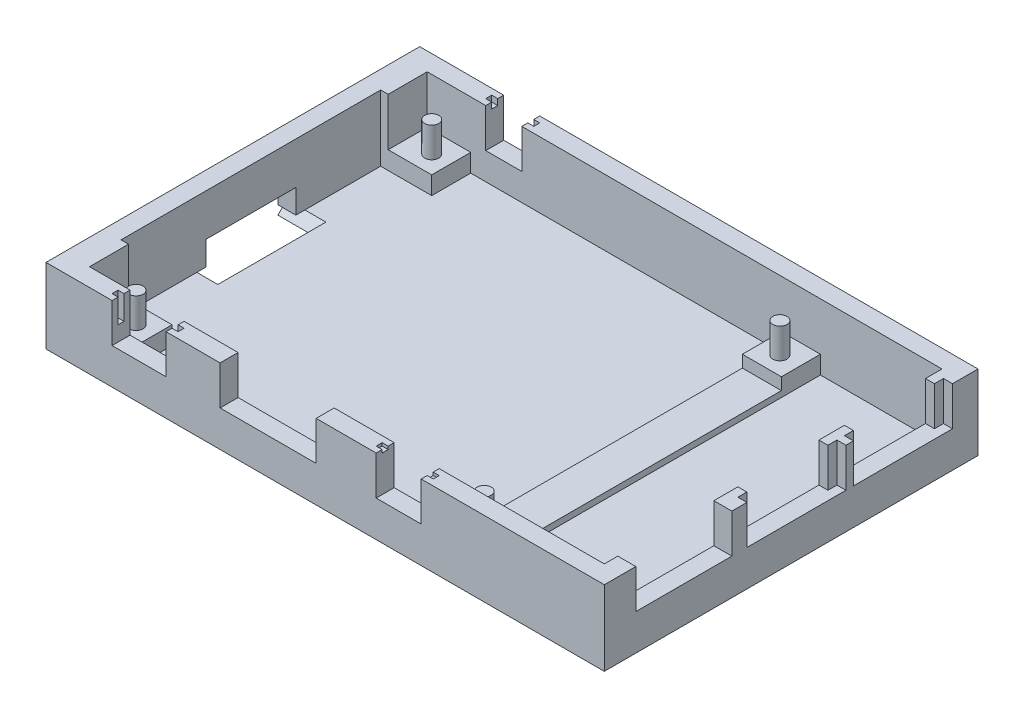
SolidWorks part; units mm, degrees
ref_plane "Front Plane" through (0, 0, 0) normal (0, 0, 1) x (1, 0, 0)
ref_plane "Top Plane" through (0, 0, 0) normal (0, 1, 0) x (1, 0, 0)
ref_plane "Right Plane" through (0, 0, 0) normal (1, 0, 0) x (0, 0, -1)
sketch "Sketch1" plane through (0, 0, 0) normal (0, 1, 0) x (1, 0, 0)
  line L1 (0, 0) -> (85, 0)
  line L2 (0, 0) -> (0, 56.25)
  line L3 (0, 56.25) -> (85, 56.25)
  line L4 (85, 0) -> (85, 56.25)
  dimension "D1" = 85
  dimension "D2" = 56.25
extrude "Boss-Extrude1" add sketch "Sketch1" along normal blind 1.5
sketch "Sketch2" plane through (0, 1.5, 0) normal (0, 1, 0) x (1, 0, 0)
  line L0 (0, 0) -> (85, 0) construction
  line L1 (0, 0) -> (6.5, 0)
  line L2 (0, 0) -> (0, 6.5)
  line L3 (0, 6.5) -> (6.5, 6.5)
  line L4 (6.5, 0) -> (6.5, 6.5)
  line L5 (58.25, 0) -> (64.75, 0)
  line L6 (58.25, 0) -> (58.25, 6.5)
  line L7 (58.25, 6.5) -> (64.75, 6.5)
  line L8 (64.75, 0) -> (64.75, 6.5)
  line L9 (61.5, 6.5) -> (61.5, 0) construction
  line L10 (0, 28.125) -> (85, 28.125) construction
  line L11 (0, 56.25) -> (0, 0) construction
  line L12 (85, 0) -> (85, 56.25) construction
  line L13 (61.5, 49.75) -> (61.5, 56.25) construction
  line L14 (64.75, 56.25) -> (64.75, 49.75)
  line L15 (58.25, 49.75) -> (64.75, 49.75)
  line L16 (58.25, 56.25) -> (58.25, 49.75)
  line L17 (58.25, 56.25) -> (64.75, 56.25)
  line L18 (6.5, 56.25) -> (6.5, 49.75)
  line L19 (0, 49.75) -> (6.5, 49.75)
  line L20 (0, 56.25) -> (0, 49.75)
  line L21 (0, 56.25) -> (6.5, 56.25)
  dimension "D1" = 6.5
  dimension "D2" = 6.5
  dimension "D3" = 6.5
  dimension "D4" = 61.5
extrude "Boss-Extrude2" add sketch "Sketch2" along normal blind 3
sketch "Sketch3" plane through (0, 4.5, 0) normal (0, 1, 0) x (1, 0, 0)
  line L0 (0, 6.5) -> (0, 0) construction
  line L3 (0, 28.125) -> (85, 28.125) construction
  line L4 (0, 49.75) -> (0, 6.5) construction
  line L5 (85, 0) -> (85, 56.25) construction
  line L6 (0, 0) -> (6.5, 0) construction
  line L9 (61.5, 0) -> (61.5, 6.5) construction
  line L12 (58.25, 0) -> (64.75, 0) construction
  line L13 (64.75, 6.5) -> (58.25, 6.5) construction
  circle A0 centre (3.5, 3.5) radius 1.175
  circle A1 centre (61.5, 3.5) radius 1.175
  circle A2 centre (61.5, 52.75) radius 1.175
  circle A3 centre (3.5, 52.75) radius 1.175
  dimension "D1" = 2.35
  dimension "D2" = 2.35
  dimension "D3" = 3.5
  dimension "D4" = 3.5
extrude "Boss-Extrude3" add sketch "Sketch3" along normal blind 5
sketch "Sketch4" plane through (0, 0, 0) normal (-1, 0, 0) x (0, 0, 1)
  line L0 (0, 4.5) -> (0, 0) construction
  line L1 (0, 1.5) -> (-56.25, 1.5)
  line L2 (0, 1.5) -> (0, 0)
  line L3 (0, 0) -> (-56.25, 0)
  line L4 (-56.25, 1.5) -> (-56.25, 0)
  dimension "D1" = 1.5
extrude "Boss-Extrude4" add sketch "Sketch4" along normal blind 5
sketch "Sketch5" plane through (0, 1.5, 0) normal (0, 1, 0) x (1, 0, 0)
  line L0 (-5, 56.25) -> (0, 56.25) construction
  line L1 (-5, 0) -> (-2.5, 0)
  line L2 (-5, 0) -> (-5, 56.25)
  line L3 (-5, 56.25) -> (-2.5, 56.25)
  line L4 (-2, 6.5) -> (-2, 49.75)
  line L6 (-2.5, 0) -> (0, 0)
  line L8 (-2, 6.5) -> (0, 6.5)
  line L9 (0, 0) -> (0, 6.5)
  line L10 (-2.5, 56.25) -> (0, 56.25)
  line L12 (-2, 49.75) -> (0, 49.75)
  line L13 (0, 56.25) -> (0, 49.75)
  dimension "D1" = 2
extrude "Boss-Extrude5" add sketch "Sketch5" along normal blind 11
sketch "Sketch6" plane through (0, 0, 0) normal (0, 1, 0) x (1, 0, 0)
  line L0 (85, 0) -> (85, 56.25) construction
  line L1 (-5, 0) -> (85, 0)
  line L2 (-5, 0) -> (-5, -3)
  line L3 (-5, -3) -> (85, -3)
  line L4 (85, 0) -> (85, -3)
  line L5 (85, 56.25) -> (64.75, 56.25) construction
  line L6 (85, -3) -> (88, -3)
  line L7 (85, -3) -> (85, 56.25)
  line L8 (85, 56.25) -> (88, 56.25)
  line L9 (88, -3) -> (88, 56.25)
  line L10 (-5, 56.25) -> (-5, 0) construction
  line L11 (88, 56.25) -> (-5, 56.25)
  line L12 (88, 56.25) -> (88, 59.25)
  line L13 (88, 59.25) -> (-5, 59.25)
  line L14 (-5, 56.25) -> (-5, 59.25)
  dimension "D1" = 3
  dimension "D2" = 3
  dimension "D3" = 3
extrude "Boss-Extrude6" add sketch "Sketch6" along normal up to surface (12.5 mm away) contours L12 L11 L14 L13 | L7 L6 L9 L8 | L2 L1 L4 L3 up to face at (-1.75, 12.5, -28.125)
sketch "Sketch7" plane through (0, 12.5, 0) normal (0, 1, 0) x (1, 0, 0)
  line L0 (-5, 59.25) -> (88, 59.25) construction
  line L1 (9, 59.25) -> (15, 59.25)
  line L2 (9, 59.25) -> (9, 56.25)
  line L3 (9, 56.25) -> (15, 56.25)
  line L4 (15, 59.25) -> (15, 56.25)
  line L5 (0, 56.25) -> (85, 56.25) construction
  line L6 (86.5, 40) -> (86.5, 38.5)
  line L7 (0, 49.75) -> (0, 56.25) construction
  line L8 (85, 0) -> (0, 0) construction
  line L9 (6, 0) -> (15, 0)
  line L10 (6, 0) -> (6, -3)
  line L11 (6, -3) -> (15, -3)
  line L12 (15, 0) -> (15, -3)
  line L13 (88, -3) -> (-5, -3) construction
  line L14 (0, 0) -> (0, 6.5) construction
  line L15 (88, 59.25) -> (88, -3) construction
  line L16 (24, 0) -> (40, 0)
  line L17 (24, 0) -> (24, -3)
  line L18 (24, -3) -> (40, -3)
  line L19 (40, 0) -> (40, -3)
  line L20 (50, 0) -> (57.5, 0)
  line L21 (50, 0) -> (50, -3)
  line L22 (50, -3) -> (57.5, -3)
  line L23 (57.5, 0) -> (57.5, -3)
  line L24 (88, 2.25) -> (85, 2.25)
  line L25 (88, 2.25) -> (88, 18.25)
  line L26 (88, 18.25) -> (85, 18.25)
  line L27 (85, 2.25) -> (85, 18.25)
  line L28 (85, 56.25) -> (85, 0) construction
  line L29 (86.5, 35.75) -> (86.5, 37.25)
  line L30 (85, 35.75) -> (86.5, 35.75)
  line L31 (85, 35.75) -> (85, 22.25)
  line L32 (85, 22.25) -> (86.5, 22.25)
  line L34 (88, 20.75) -> (86.5, 20.75)
  line L35 (88, 20.75) -> (88, 37.25)
  line L36 (88, 37.25) -> (86.5, 37.25)
  line L37 (86.5, 20.75) -> (86.5, 22.25)
  line L38 (85, 53.5) -> (86.5, 53.5)
  line L39 (85, 53.5) -> (85, 40)
  line L40 (85, 40) -> (86.5, 40)
  line L42 (88, 55) -> (86.5, 55)
  line L43 (88, 55) -> (88, 38.5)
  line L44 (88, 38.5) -> (86.5, 38.5)
  line L45 (86.5, 55) -> (86.5, 53.5)
  point P28 (40, -1.5)
  point P41 (85.75, 22.25)
  dimension "D1" = 9
  dimension "D2" = 6
  dimension "D3" = 6
  dimension "D4" = 9
  dimension "D5" = 9
  dimension "D6" = 16
  dimension "D7" = 10
  dimension "D8" = 7.5
  dimension "D9" = 2.25
  dimension "D10" = 16
  dimension "D11" = 1.5
  dimension "D12" = 4
  dimension "D13" = 13.5
  dimension "D14" = 1.5
  dimension "D15" = 1.5
  dimension "D16" = 13.5
  dimension "D17" = 4.25
  dimension "D18" = 1.5
  dimension "D19" = 1.5
  dimension "D21" = 1.5
extrude "Cut-Extrude1" cut sketch "Sketch7" against normal offset from surface (6.5 mm away) 1.5 up to face at (61.5, 4.5, -53.925)
sketch "Sketch8" plane through (-5, 0, 0) normal (-1, 0, 0) x (0, 0, 1)
  line L0 (-59.25, 0) -> (3, 0) construction
  line L1 (-35.625, 0) -> (-20.625, 0)
  line L2 (-35.625, 1.5) -> (-35.625, 5.5)
  line L3 (-35.625, 5.5) -> (-20.625, 5.5)
  line L4 (-20.625, 1.5) -> (-20.625, 5.5)
  line L5 (-6.5, 4.5) -> (0, 4.5) construction
  line L6 (-28.125, 5.5) -> (-28.125, 0) construction
  line L7 (-35.625, 0) -> (-37.125, 1.5)
  line L8 (-37.125, 1.5) -> (-35.625, 1.5)
  line L9 (-19.125, 1.5) -> (-20.625, 1.5)
  line L10 (-20.625, 0) -> (-19.125, 1.5)
  point P8 (-28.125, 0)
  point P9 (-28.125, 0)
  dimension "D1" = 1
  dimension "D2" = 15
  dimension "D3" = 1.5
  dimension "D4" = 1.5
extrude "Cut-Extrude2" cut sketch "Sketch8" against normal offset from surface (6.5 mm away) 1.5 up to face at (0, 8.5, -53) offset beyond the face yes
sketch "Sketch9" plane through (0, 1.5, 0) normal (0, 1, 0) x (1, 0, 0)
  line L7 (58.25, 6.5) -> (64.75, 6.5)
  line L8 (58.25, 6.5) -> (58.25, 49.75)
  line L9 (58.25, 49.75) -> (64.75, 49.75)
  line L10 (64.75, 6.5) -> (64.75, 49.75)
extrude "Boss-Extrude7" add sketch "Sketch9" along normal blind 1
sketch "Sketch10" plane through (0, 12.5, 0) normal (0, 1, 0) x (1, 0, 0)
  line L7 (50, -3) -> (40, -3) construction
  line L8 (49, -1) -> (58.5, -1)
  line L9 (49, -1) -> (49, -2)
  line L10 (49, -2) -> (58.5, -2)
  line L11 (58.5, -1) -> (58.5, -2)
  line L12 (50, 0) -> (50, -3) construction
  line L13 (57.5, -3) -> (57.5, 0) construction
  dimension "D1" = 1
  dimension "D2" = 1
  dimension "D3" = 1
  dimension "D4" = 1
extrude "Cut-Extrude3" cut sketch "Sketch10" against normal offset from surface (0.5 mm away) 7.5 up to face at (61.5, 4.5, -4.675)
sketch "Sketch11" plane through (0, 12.5, 0) normal (0, 1, 0) x (1, 0, 0)
  line L0 (6, -3) -> (-5, -3) construction
  line L1 (5, -1) -> (16, -1)
  line L2 (5, -1) -> (5, -2)
  line L3 (5, -2) -> (16, -2)
  line L4 (16, -1) -> (16, -2)
  line L5 (6, 0) -> (6, -3) construction
  line L6 (15, -3) -> (15, 0) construction
  dimension "D1" = 1
  dimension "D2" = 1
  dimension "D3" = 1
  dimension "D4" = 1
extrude "Cut-Extrude4" cut sketch "Sketch11" against normal offset from surface (4 mm away) 4 up to face at (3.5, 4.5, -4.675)
sketch "Sketch12" plane through (0, 12.5, 0) normal (0, 1, 0) x (1, 0, 0)
  line L0 (15, 56.25) -> (15, 59.25) construction
  line L1 (8, 58.25) -> (16, 58.25)
  line L2 (8, 58.25) -> (8, 57.25)
  line L3 (8, 57.25) -> (16, 57.25)
  line L4 (16, 58.25) -> (16, 57.25)
  line L5 (15, 59.25) -> (88, 59.25) construction
  line L6 (9, 59.25) -> (9, 56.25) construction
  dimension "D1" = 1
  dimension "D2" = 1
  dimension "D3" = 1
  dimension "D4" = 1
extrude "Cut-Extrude5" cut sketch "Sketch12" against normal offset from surface (1 mm away) 7 up to face at (3.5, 4.5, -53.925)
sketch "Sketch13" plane through (0, 12.5, 0) normal (0, 1, 0) x (1, 0, 0)
  line L0 (6.5, 56.25) -> (0, 56.25) construction
  line L1 (0, 0) -> (-0.75, 0)
  line L2 (0, 0) -> (0, 56.25)
  line L3 (0, 56.25) -> (-0.75, 56.25)
  line L4 (-0.75, 0) -> (-0.75, 56.25)
  dimension "D1" = 0.75
extrude "Cut-Extrude6" cut sketch "Sketch13" against normal up to surface (8 mm away) up to face at (3.5, 4.5, -4.675)
